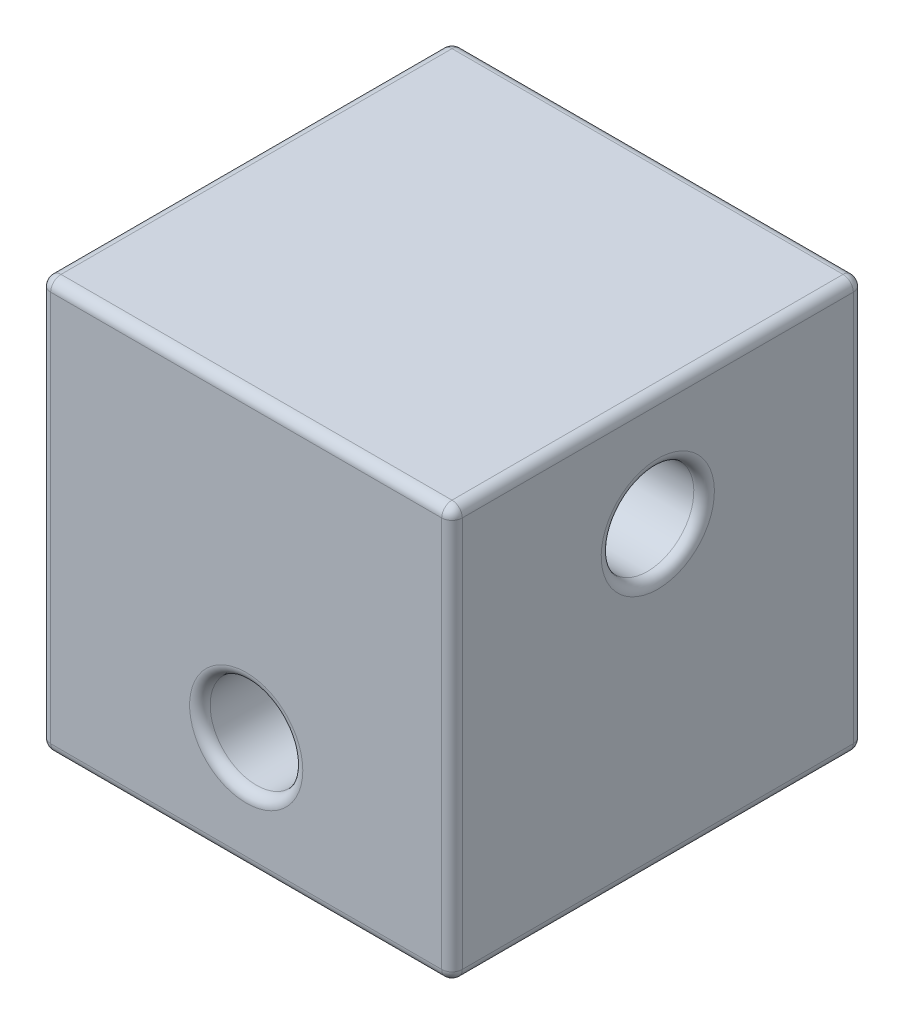
SolidWorks part; units mm, degrees
ref_plane "Front Plane" through (0, 0, 0) normal (0, 0, 1) x (1, 0, 0)
ref_plane "Top Plane" through (0, 0, 0) normal (0, 1, 0) x (1, 0, 0)
ref_plane "Right Plane" through (0, 0, 0) normal (1, 0, 0) x (0, 0, -1)
sketch "Sketch1" plane through (0, 0, 0) normal (0, 0, 1) x (1, 0, 0)
  line L1 (-20, 20) -> (20, 20)
  line L2 (-20, 20) -> (-20, -20)
  line L3 (-20, -20) -> (20, -20)
  line L4 (20, 20) -> (20, -20)
  line L5 (-20, 20) -> (20, -20) construction
  line L6 (-20, -20) -> (20, 20) construction
  point P0 (0, 0)
  dimension "D1" = 40
  dimension "D2" = 40
extrude "Boss-Extrude1" add sketch "Sketch1" along normal mid plane 40
sketch "Sketch2" plane through (0, 0, 20) normal (0, 0, 1) x (1, 0, 0)
  line L0 (0, 13.6388) -> (0, -9.4213) construction
  circle A0 centre (0, -9) radius 4.5
  dimension "D1" = 9
  dimension "D2" = 9
extrude "Cut-Extrude1" cut sketch "Sketch2" against normal through all
sketch "Sketch3" plane through (-20, 0, 0) normal (-1, 0, 0) x (0, 0, 1)
  line L0 (0, 17.6012) -> (0, -12.9076) construction
  circle A0 centre (0, 9) radius 4.5
  dimension "D1" = 9
  dimension "D2" = 9
extrude "Cut-Extrude2" cut sketch "Sketch3" against normal through all
fillet "Fillet1" radius 1 16 edges at (0, -20, -20) (20, -20, 0) (20, 0, -20) (20, 4.5, 0) (20, 20, 0) (0, 20, -20) (0, -20, 20) (0, 20, 20) (20, 0, 20) (4.5, -9, 20) (-20, 20, 0) (-20, 0, 20) (-20, -20, 0) (-20, 0, -20) (-20, 4.5, 0) (4.5, -9, -20)
